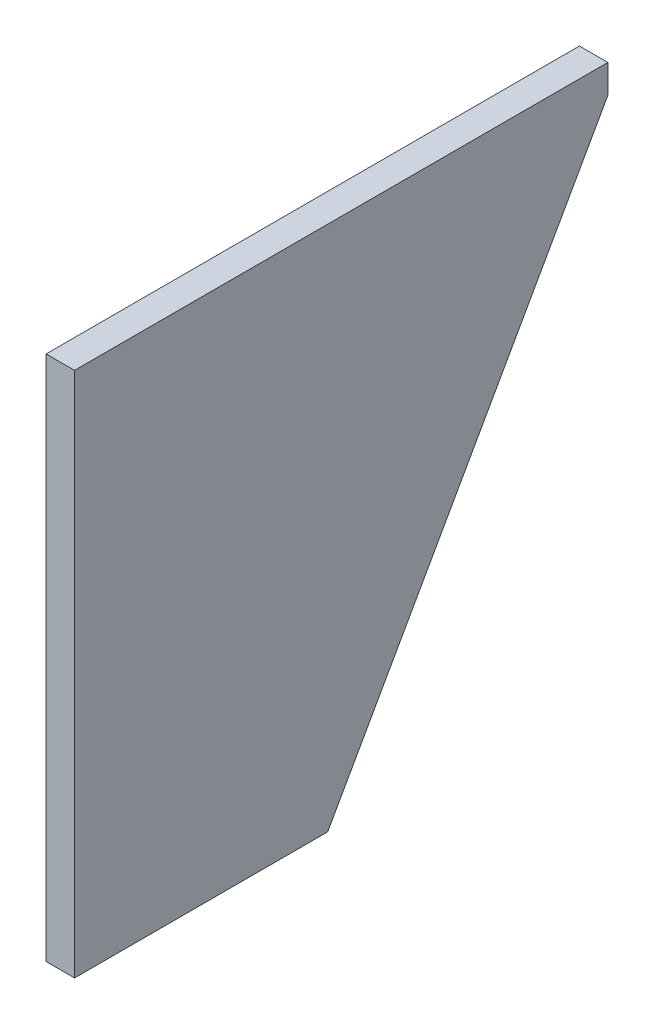
SolidWorks part; units mm, degrees
ref_plane "Alzado" through (0, 0, 0) normal (0, 0, 1) x (1, 0, 0)
ref_plane "Planta" through (0, 0, 0) normal (0, 1, 0) x (1, 0, 0)
ref_plane "Vista lateral" through (0, 0, 0) normal (1, 0, 0) x (0, 0, -1)
ref_plane "Plano1" through (-192.7541, 0, 0) normal (-1, 0, 0) x (0, 0, 1)
sketch "Croquis2" plane through (-192.7541, 0, 0) normal (-1, 0, 0) x (0, 0, 1)
  line L0 (360, 202.8344) -> (360, -167.1656)
  line L1 (360, -167.1656) -> (182, -167.1656)
  line L2 (182, -167.1656) -> (-15, 182.8344)
  line L3 (-15, 182.8344) -> (-15, 202.8344)
  line L4 (-15, 202.8344) -> (360, 202.8344)
extrude "Saliente-Extruir1" add sketch "Croquis2" against normal blind 20
